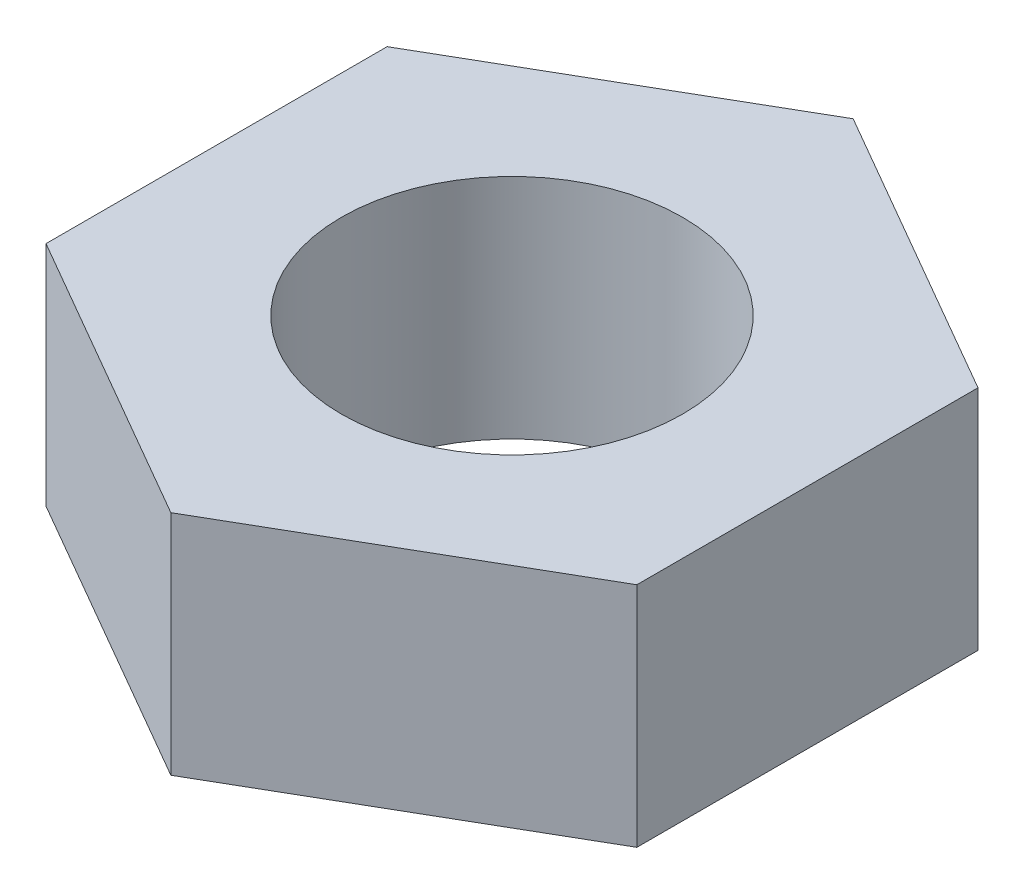
SolidWorks part; units mm, degrees
ref_plane "Alzado" through (0, 0, 0) normal (0, 0, 1) x (1, 0, 0)
ref_plane "Planta" through (0, 0, 0) normal (0, 1, 0) x (1, 0, 0)
ref_plane "Vista lateral" through (0, 0, 0) normal (1, 0, 0) x (0, 0, -1)
sketch "Croquis1" plane through (0, 0, 0) normal (0, 1, 0) x (1, 0, 0)
  line L0 (-2.5981, 1.5) -> (2.5981, -1.5) construction
  line L1 (0, 3) -> (0, -3) construction
  line L2 (2.5981, 1.5) -> (-2.5981, -1.5) construction
  line L3 (-2.5981, 1.5) -> (-2.5981, -1.5)
  line L4 (-2.5981, -1.5) -> (0, -3)
  line L5 (0, -3) -> (2.5981, -1.5)
  line L6 (2.5981, -1.5) -> (2.5981, 1.5)
  line L7 (2.5981, 1.5) -> (0, 3)
  line L8 (0, 3) -> (-2.5981, 1.5)
  line L9 (0, 0) -> (0, 1.9342) construction
  circle A0 centre (0, 0) radius 3 construction
  dimension "D1" = 6
  dimension "D2" = 60
  dimension "D3" = 60
extrude "Saliente-Extruir1" add sketch "Croquis1" along normal blind 2 contours L4 L5 L6 L7 L8 L3
sketch "Croquis2" plane through (0, 0, 0) normal (0, -1, 0) x (1, 0, 0)
  circle A0 centre (0, 0) radius 1.5
  dimension "D1" = 3
sketch "Croquis3" plane through (0, 2, 0) normal (0, 1, 0) x (1, 0, 0)
  circle A0 centre (0, 0) radius 1.5
  dimension "D1" = 3
extrude "Cortar-Extruir1" cut sketch "Croquis3" against normal blind 6
